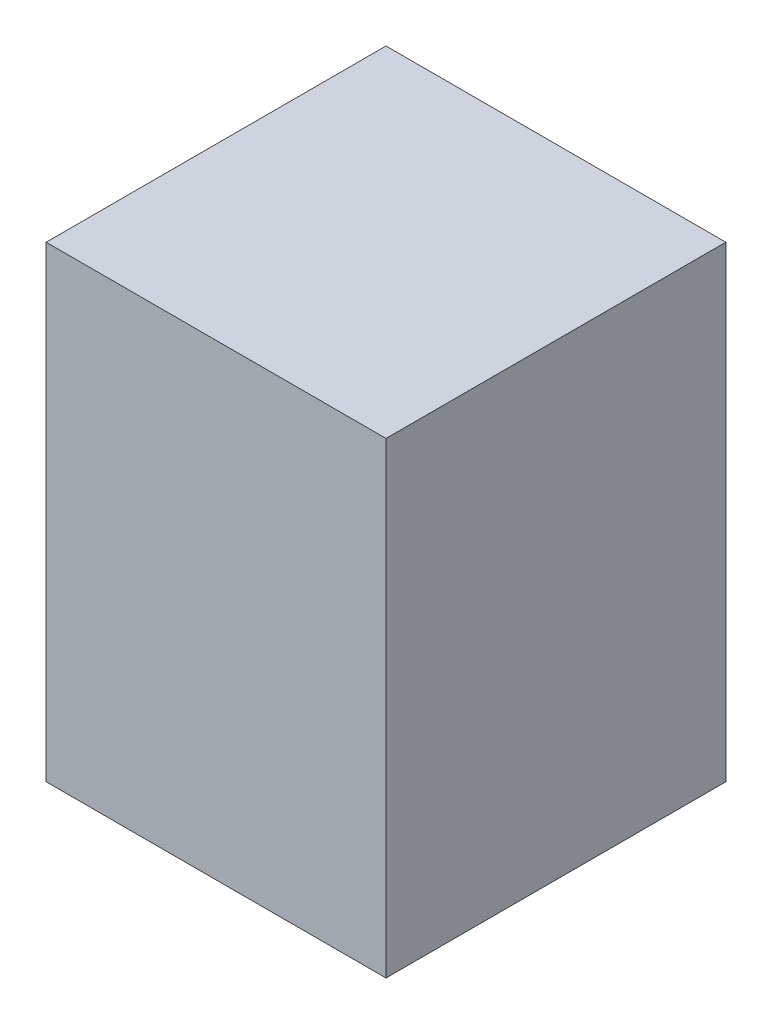
SolidWorks part; units mm, degrees
ref_plane "Front Plane" through (0, 0, 0) normal (0, 0, 1) x (1, 0, 0)
ref_plane "Top Plane" through (0, 0, 0) normal (0, 1, 0) x (1, 0, 0)
ref_plane "Right Plane" through (0, 0, 0) normal (1, 0, 0) x (0, 0, -1)
sketch "Sketch1" plane through (0, 0, 0) normal (1, 0, 0) x (0, 0, -1)
  line L1 (0, 0) -> (5.08, 0)
  line L2 (0, 0) -> (0, 6.985)
  line L3 (0, 6.985) -> (5.08, 6.985)
  line L4 (5.08, 0) -> (5.08, 6.985)
  dimension "D1" = 5.08
  dimension "D2" = 6.985
extrude "Boss-Extrude1" add sketch "Sketch1" along normal blind 5.08
